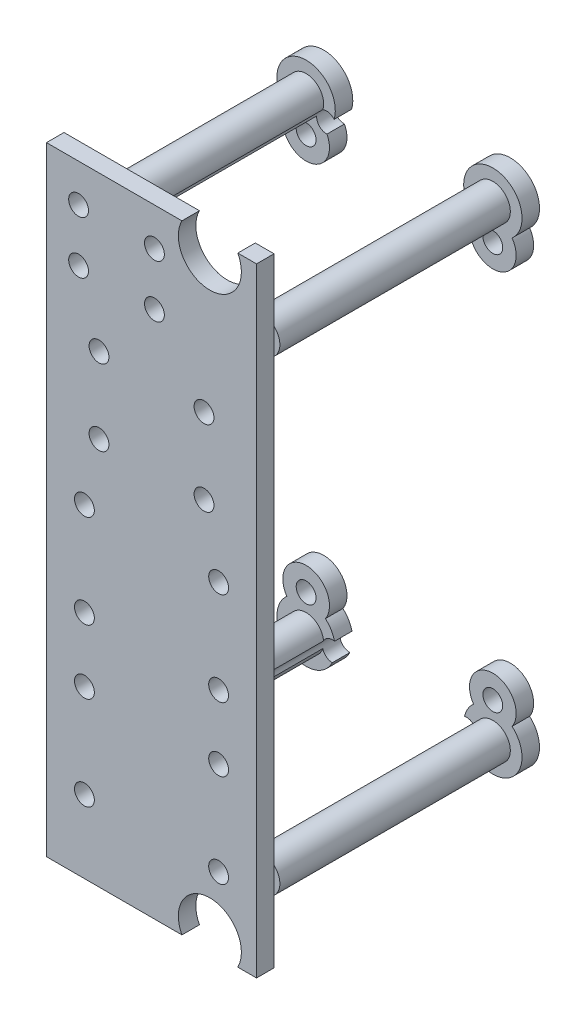
SolidWorks part; units mm, degrees
other "I2C Interface Shelf"
ref_plane "Front Plane" through (0, 0, 0) normal (0, 0, 1) x (1, 0, 0)
ref_plane "Top Plane" through (0, 0, 0) normal (0, 1, 0) x (1, 0, 0)
ref_plane "Right Plane" through (0, 0, 0) normal (1, 0, 0) x (0, 0, -1)
sketch3d "Main Profile Sketch datum points"
  point P0 (0, 0, 94)
  point P1 (10, 0, 94)
  point P2 (0, 10, 94)
ref_plane "Main Profile Sketch plane" through (0, 0, 94) normal (0, 0, 1) x (1, 0, 0)
sketch "Main Profile Sketch" plane through (0, 0, 94) normal (0, 0, 1) x (1, 0, 0)
  line L0 (182, 53) -> (205.2136, 53)
  line L1 (214.7864, 53) -> (218, 53)
  line L2 (218, 53) -> (218, -53)
  line L3 (214.7864, -53) -> (218, -53)
  line L4 (182, -53) -> (205.2136, -53)
  line L5 (182, 53) -> (182, -53)
  arc A0 (205.2136, 53) -> (214.7864, 53) centre (210, 50.5) ccw
  arc A1 (214.7864, -53) -> (205.2136, -53) centre (210, -50.5) ccw
  circle A2 centre (188.5, -40.5) radius 1.7
  circle A3 centre (188.5, -24.5) radius 1.7
  circle A4 centre (188.5, -13.5) radius 1.7
  circle A5 centre (211.5, -40.5) radius 1.7
  circle A6 centre (211.5, -24.5) radius 1.7
  circle A7 centre (211.5, -13.5) radius 1.7
  circle A8 centre (188.5, 2.5) radius 1.7
  circle A9 centre (191, 13.5) radius 1.7
  circle A10 centre (187.5, 37.5) radius 1.7
  circle A11 centre (187.5, 46.5) radius 1.7
  circle A12 centre (191, 26.5) radius 1.7
  circle A13 centre (211.5, 2.5) radius 1.7
  circle A14 centre (209, 13.5) radius 1.7
  circle A15 centre (200.5, 37.5) radius 1.7
  circle A16 centre (200.5, 46.5) radius 1.7
  circle A17 centre (209, 26.5) radius 1.7
extrude "Main Extrusion" add sketch "Main Profile Sketch" against normal blind 3 separate body
sketch3d "Detail Profile 2 Sketch datum points"
  point P0 (0, 0, 91)
  point P1 (10, 0, 91)
  point P2 (0, 10, 91)
ref_plane "Detail Profile 2 Sketch plane" through (0, 0, 91) normal (0, 0, 1) x (1, 0, 0)
sketch "Detail Profile 2 Sketch" plane through (0, 0, 91) normal (0, 0, 1) x (1, 0, 0)
  arc A0 (186.8792, 40.8428) -> (184.1365, 37.0031) centre (187.5, 37.5) ccw
  arc A1 (186.8792, 40.8428) -> (184.1365, 37.0031) centre (184, 40) ccw
  circle A2 centre (216, 40) radius 3
  arc A3 (186.2178, -37.9798) -> (185.7202, -42.4578) centre (188.5, -40.5) ccw
  arc A4 (186.2178, -37.9798) -> (185.7202, -42.4578) centre (184, -40) ccw
  arc A5 (214.2798, -42.4578) -> (213.7822, -37.9798) centre (211.5, -40.5) ccw
  arc A6 (214.2798, -42.4578) -> (213.7822, -37.9798) centre (216, -40) ccw
extrude "Detail Extrusion 2" add sketch "Detail Profile 2 Sketch" against normal blind 3.2
sketch3d "Detail Profile 3 Sketch datum points"
  point P0 (0, 0, 87.8)
  point P1 (10, 0, 87.8)
  point P2 (0, 10, 87.8)
ref_plane "Detail Profile 3 Sketch plane" through (0, 0, 87.8) normal (0, 0, 1) x (1, 0, 0)
sketch "Detail Profile 3 Sketch" plane through (0, 0, 87.8) normal (0, 0, 1) x (1, 0, 0)
  arc A0 (186.8529, 39.072) -> (185.8031, 37.6023) centre (187.5, 37.5) ccw
  arc A1 (186.8529, 39.072) -> (185.8031, 37.6023) centre (184, 40) ccw
  circle A2 centre (216, 40) radius 3
  arc A3 (186.9873, -39.7243) -> (186.8539, -40.9247) centre (188.5, -40.5) ccw
  arc A4 (186.9873, -39.7243) -> (186.8539, -40.9247) centre (184, -40) ccw
  arc A5 (213.1461, -40.9247) -> (213.0127, -39.7243) centre (211.5, -40.5) ccw
  arc A6 (213.1461, -40.9247) -> (213.0127, -39.7243) centre (216, -40) ccw
extrude "Detail Extrusion 3" add sketch "Detail Profile 3 Sketch" against normal blind 36.3
sketch3d "Detail Profile 4 Sketch datum points"
  point P0 (0, 0, 51.5)
  point P1 (10, 0, 51.5)
  point P2 (0, 10, 51.5)
ref_plane "Detail Profile 4 Sketch plane" through (0, 0, 51.5) normal (0, 0, 1) x (1, 0, 0)
sketch "Detail Profile 4 Sketch" plane through (0, 0, 51.5) normal (0, 0, 1) x (1, 0, 0)
  arc A0 (188.799, 38.5966) -> (187.5714, 35.8015) centre (187.5, 37.5) ccw
  arc A1 (180.6928, 36.25) -> (187.5714, 35.8015) centre (184, 34) ccw
  arc A2 (188.799, 38.5966) -> (180.6928, 36.25) centre (184, 40) ccw
  circle A3 centre (184, 34) radius 1.7
  arc A4 (188.8634, -38.8393) -> (188.49, -42.2) centre (188.5, -40.5) ccw
  arc A5 (180.6928, -36.25) -> (188.49, -42.2) centre (184, -40) ccw
  arc A6 (187.3072, -36.25) -> (180.6928, -36.25) centre (184, -34) ccw
  arc A7 (188.8634, -38.8393) -> (187.3072, -36.25) centre (184, -40) ccw
  circle A8 centre (184, -34) radius 1.7
  arc A9 (211.51, -42.2) -> (211.1366, -38.8393) centre (211.5, -40.5) ccw
  arc A10 (212.6928, -36.25) -> (211.1366, -38.8393) centre (216, -40) ccw
  arc A11 (219.3072, -36.25) -> (212.6928, -36.25) centre (216, -34) ccw
  arc A12 (211.51, -42.2) -> (219.3072, -36.25) centre (216, -40) ccw
  circle A13 centre (216, -34) radius 1.7
  arc A14 (212.6928, 36.25) -> (219.3072, 36.25) centre (216, 34) ccw
  arc A15 (219.3072, 36.25) -> (212.6928, 36.25) centre (216, 40) ccw
  circle A16 centre (216, 34) radius 1.7
extrude "Detail Extrusion 4" add sketch "Detail Profile 4 Sketch" against normal blind 3
